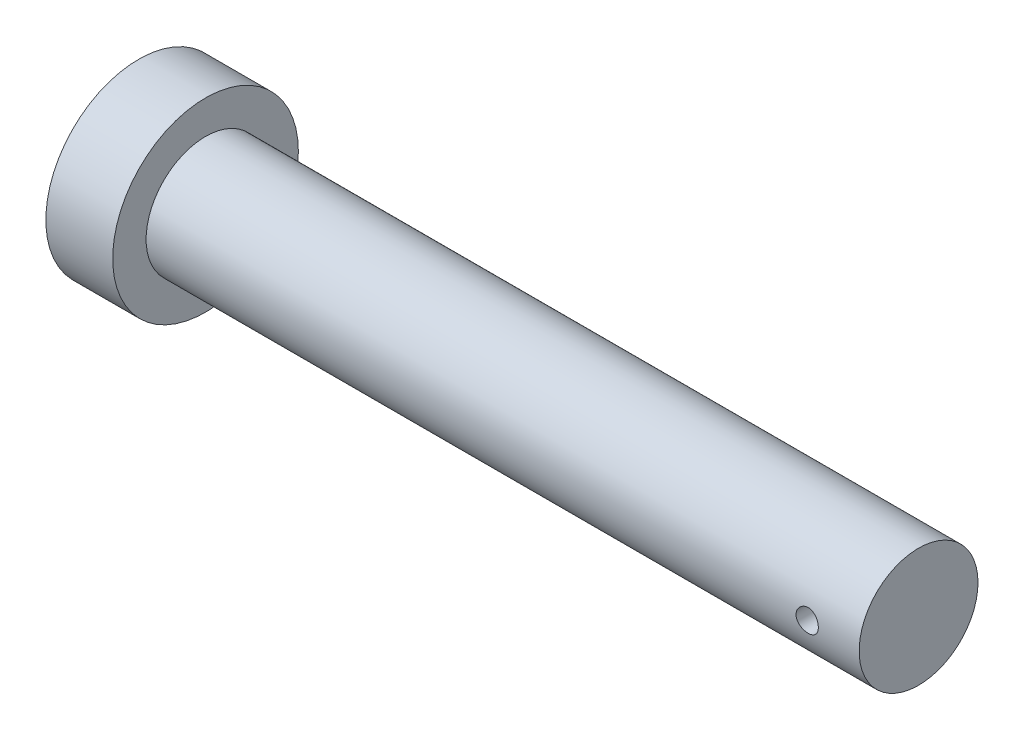
SolidWorks part; units mm, degrees
material "AISI 4130 Steel, normalized at 870C"
ref_plane "Front Plane" through (0, 0, 0) normal (0, 0, 1) x (1, 0, 0)
ref_plane "Top Plane" through (0, 0, 0) normal (0, 1, 0) x (1, 0, 0)
ref_plane "Right Plane" through (0, 0, 0) normal (1, 0, 0) x (0, 0, -1)
sketch "Sketch1" plane through (0, 0, 0) normal (1, 0, 0) x (0, 0, -1)
  circle A0 centre (0, 0) radius 12.5
extrude "Boss-Extrude1" add sketch "Sketch1" along normal blind 9
sketch "Sketch2" plane through (9, 0, 0) normal (1, 0, 0) x (0, 0, -1)
  circle A0 centre (0, 0) radius 8
extrude "Boss-Extrude2" add sketch "Sketch2" along normal blind 96
sketch "Sketch3" plane through (105, 0, 0) normal (1, 0, 0) x (0, 0, -1)
  line L0 (-8, 0) -> (8, 0) construction
  circle A0 centre (0, 0) radius 8 construction
ref_plane "Plane1" through (0, 0, 8) normal (0, 0, 1) x (1, 0, 0)
sketch "Sketch4" plane through (0, 0, 8) normal (0, 0, 1) x (1, 0, 0)
  line L0 (9, -8) -> (9, 8) construction
  circle A0 centre (98, 0) radius 1.5
  dimension "D1" = 89
extrude "Cut-Extrude1" cut sketch "Sketch4" against normal blind 96
